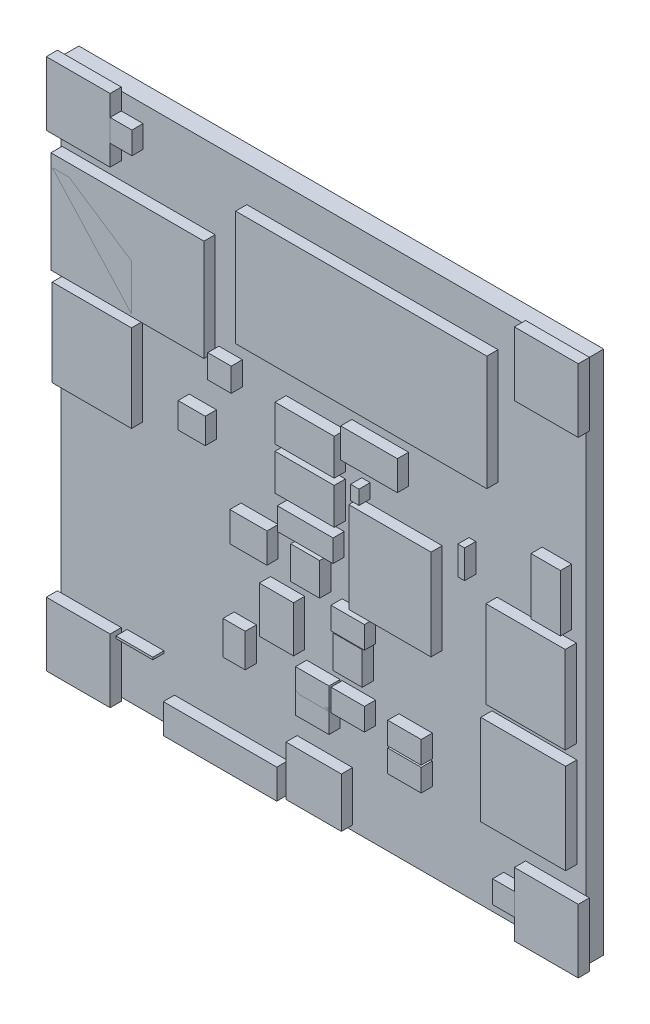
SolidWorks part; units mm, degrees
ref_plane "Front Plane" through (0, 0, 0) normal (0, 0, 1) x (1, 0, 0)
ref_plane "Top Plane" through (0, 0, 0) normal (0, 1, 0) x (1, 0, 0)
ref_plane "Right Plane" through (0, 0, 0) normal (1, 0, 0) x (0, 0, -1)
sketch "Sketch1" plane through (0, 0, 0) normal (0, 0, 1) x (1, 0, 0)
  line L0 (0, 46.99) -> (46.99, 46.99)
  line L1 (46.99, 46.99) -> (46.99, 0)
  line L2 (46.99, 0) -> (0, 0)
  line L3 (0, 0) -> (0, 46.99)
extrude "BOARD" add sketch "Sketch1" along normal blind 1.6 separate body
ref_plane "Plane1" through (0, 0, 1.6) normal (0, 0, 1) x (1, 0, 0)
sketch "Sketch2" plane through (0, 0, 1.6) normal (0, 0, 1) x (1, 0, 0)
  line L0 (16.1165, 20.4135) -> (19.4435, 20.4135)
  line L1 (19.4435, 20.4135) -> (19.4435, 17.75)
  line L2 (19.4435, 17.75) -> (16.1165, 17.75)
  line L3 (16.1165, 17.75) -> (16.1165, 20.4135)
extrude "1210-1" add sketch "Sketch2" along normal blind 1 separate body
sketch "Sketch3" plane through (0, 0, 1.6) normal (0, 0, 1) x (1, 0, 0)
  line L0 (25.3584, 20.8356) -> (20.3616, 20.8356)
  line L1 (20.3616, 20.8356) -> (20.3616, 22.827)
  line L2 (20.3616, 22.827) -> (25.3584, 22.827)
  line L3 (25.3584, 22.827) -> (25.3584, 20.8356)
extrude "1206-1" add sketch "Sketch3" along normal blind 1 separate body
sketch "Sketch4" plane through (0, 0, 1.6) normal (0, 0, 1) x (1, 0, 0)
  line L0 (20.1584, 30.76) -> (25.46, 30.76)
  line L1 (25.46, 30.76) -> (25.46, 27.5084)
  line L2 (25.46, 27.5084) -> (20.1584, 27.5084)
  line L3 (20.1584, 27.5084) -> (20.1584, 30.76)
extrude "EIA3528-1" add sketch "Sketch4" along normal blind 1 separate body
sketch "Sketch5" plane through (0, 0, 1.6) normal (0, 0, 1) x (1, 0, 0)
  line L0 (20.1584, 26.95) -> (25.46, 26.95)
  line L1 (25.46, 26.95) -> (25.46, 23.6984)
  line L2 (25.46, 23.6984) -> (20.1584, 23.6984)
  line L3 (20.1584, 23.6984) -> (20.1584, 26.95)
extrude "EIA3528-2" add sketch "Sketch5" along normal blind 1 separate body
sketch "Sketch6" plane through (0, 0, 1.6) normal (0, 0, 1) x (1, 0, 0)
  line L0 (25.1716, 17.5184) -> (28.1684, 17.5184)
  line L1 (28.1684, 17.5184) -> (28.1684, 15.527)
  line L2 (28.1684, 15.527) -> (25.1716, 15.527)
  line L3 (25.1716, 15.527) -> (25.1716, 17.5184)
extrude "0603-CAP-1" add sketch "Sketch6" along normal blind 1 separate body
sketch "Sketch7" plane through (0, 0, 1.6) normal (0, 0, 1) x (1, 0, 0)
  line L0 (15.5016, 8.6616) -> (15.5016, 11.6584)
  line L1 (15.5016, 11.6584) -> (17.493, 11.6584)
  line L2 (17.493, 11.6584) -> (17.493, 8.6616)
  line L3 (17.493, 8.6616) -> (15.5016, 8.6616)
extrude "0603-CAP-2" add sketch "Sketch7" along normal blind 1 separate body
sketch "Sketch8" plane through (0, 0, 1.6) normal (0, 0, 1) x (1, 0, 0)
  line L0 (24.1554, 20.4724) -> (24.1554, 17.5514)
  line L1 (24.1554, 17.5514) -> (21.5646, 17.5514)
  line L2 (21.5646, 17.5514) -> (21.5646, 20.4724)
  line L3 (21.5646, 20.4724) -> (24.1554, 20.4724)
extrude "SOT23-1" add sketch "Sketch8" along normal blind 1 separate body
sketch "Sketch9" plane through (0, 0, 1.6) normal (0, 0, 1) x (1, 0, 0)
  line L0 (25.3746, 12.5476) -> (25.3746, 15.4686)
  line L1 (25.3746, 15.4686) -> (27.9654, 15.4686)
  line L2 (27.9654, 15.4686) -> (27.9654, 12.5476)
  line L3 (27.9654, 12.5476) -> (25.3746, 12.5476)
extrude "SOT23-2" add sketch "Sketch9" along normal blind 1 separate body
sketch "Sketch10" plane through (0, 0, 1.6) normal (0, 0, 1) x (1, 0, 0)
  line L0 (7.35, 43.45) -> (5.35, 43.45)
  line L1 (5.35, 43.45) -> (5.35, 45.45)
  line L2 (5.35, 45.45) -> (7.35, 45.45)
  line L3 (7.35, 45.45) -> (7.35, 43.45)
extrude "FIDUCIAL-1X2-1" add sketch "Sketch10" along normal blind 1 separate body
sketch "Sketch11" plane through (0, 0, 1.6) normal (0, 0, 1) x (1, 0, 0)
  line L0 (41.64, 1.54) -> (39.64, 1.54)
  line L1 (39.64, 1.54) -> (39.64, 3.54)
  line L2 (39.64, 3.54) -> (41.64, 3.54)
  line L3 (41.64, 3.54) -> (41.64, 1.54)
extrude "FIDUCIAL-1X2-2" add sketch "Sketch11" along normal blind 1 separate body
sketch "POWER_JACK_SMD-1 [0]" plane through (0, 0, 1.6) normal (0, 0, 1) x (1, 0, 0)
  line L0 (-0.0216, 18.5716) -> (14.88, 18.5716)
  line L1 (14.88, 18.5716) -> (14.88, 9.3684)
  line L2 (14.88, 9.3684) -> (-0.0216, 9.3684)
  line L3 (-0.0216, 9.3684) -> (-0.0216, 18.5716)
sketch "Sketch14" plane through (0, 0, 1.6) normal (0, 0, 1) x (1, 0, 0)
  line L0 (13.8016, 40.06) -> (13.8016, 30.9584)
  line L1 (13.8016, 30.9584) -> (0.1, 30.9584)
  line L2 (0.1, 30.9584) -> (0.1, 40.06)
  line L3 (0.1, 40.06) -> (13.8016, 40.06)
extrude "POWER_JACK_PTH-1" add sketch "Sketch14" along normal blind 1 separate body
sketch "Sketch15" plane through (0, 0, 1.6) normal (0, 0, 1) x (1, 0, 0)
  line L0 (46.18, 15.5316) -> (46.18, 7.43)
  line L1 (46.18, 7.43) -> (38.5784, 7.43)
  line L2 (38.5784, 7.43) -> (38.5784, 15.5316)
  line L3 (38.5784, 15.5316) -> (46.18, 15.5316)
extrude "JST-2-SMD-1" add sketch "Sketch15" along normal blind 1 separate body
sketch "Sketch16" plane through (0, 0, 1.6) normal (0, 0, 1) x (1, 0, 0)
  line L0 (20.32, -0.1016) -> (10.16, -0.1016)
  line L1 (10.16, -0.1016) -> (10.16, 2.54)
  line L2 (10.16, 2.54) -> (20.32, 2.54)
  line L3 (20.32, 2.54) -> (20.32, -0.1016)
extrude "1X04-1" add sketch "Sketch16" along normal blind 1 separate body
sketch "Sketch17" plane through (0, 0, 1.6) normal (0, 0, 1) x (1, 0, 0)
  line L0 (43.0784, 25.4) -> (43.0784, 30.48)
  line L1 (43.0784, 30.48) -> (45.72, 30.48)
  line L2 (45.72, 30.48) -> (45.72, 25.4)
  line L3 (45.72, 25.4) -> (43.0784, 25.4)
extrude "1X02-1" add sketch "Sketch17" along normal blind 1 separate body
sketch "Sketch18" plane through (0, 0, 1.6) normal (0, 0, 1) x (1, 0, 0)
  line L0 (39.0434, 16.773) -> (39.0434, 24.573)
  line L1 (39.0434, 24.573) -> (46.145, 24.573)
  line L2 (46.145, 24.573) -> (46.145, 16.773)
  line L3 (46.145, 16.773) -> (39.0434, 16.773)
extrude "SCREWTERMINAL-3_5MM-2-1" add sketch "Sketch18" along normal blind 1 separate body
sketch "Sketch19" plane through (0, 0, 1.6) normal (0, 0, 1) x (1, 0, 0)
  line L0 (7.3116, 38.98) -> (7.3116, 31.18)
  line L1 (7.3116, 31.18) -> (0.21, 31.18)
  line L2 (0.21, 31.18) -> (0.21, 38.98)
  line L3 (0.21, 38.98) -> (7.3116, 38.98)
extrude "SCREWTERMINAL-3_5MM-2-2" add sketch "Sketch19" along normal blind 1 separate body
sketch "Sketch20" plane through (0, 0, 1.6) normal (0, 0, 1) x (1, 0, 0)
  line L0 (7.3116, 30.09) -> (7.3116, 22.29)
  line L1 (7.3116, 22.29) -> (0.21, 22.29)
  line L2 (0.21, 22.29) -> (0.21, 30.09)
  line L3 (0.21, 30.09) -> (7.3116, 30.09)
extrude "SCREWTERMINAL-3_5MM-2-3" add sketch "Sketch20" along normal blind 1 separate body
sketch "Sketch21" plane through (0, 0, 1.6) normal (0, 0, 1) x (1, 0, 0)
  line L0 (11.4808, 26.543) -> (13.9192, 26.543)
  line L1 (13.9192, 26.543) -> (13.9192, 24.257)
  line L2 (13.9192, 24.257) -> (11.4808, 24.257)
  line L3 (11.4808, 24.257) -> (11.4808, 26.543)
extrude "SJ_2S-1" add sketch "Sketch21" along normal blind 1 separate body
sketch "Sketch22" plane through (0, 0, 1.6) normal (0, 0, 1) x (1, 0, 0)
  line L0 (16.24, 31.5865) -> (16.24, 29.475)
  line L1 (16.24, 29.475) -> (14.1384, 29.475)
  line L2 (14.1384, 29.475) -> (14.1384, 31.5865)
  line L3 (14.1384, 31.5865) -> (16.24, 31.5865)
extrude "SJ_2S-NO-1" add sketch "Sketch22" along normal blind 1 separate body
sketch "Sketch23" plane through (0, 0, 1.6) normal (0, 0, 1) x (1, 0, 0)
  line L0 (36.5252, 27.94) -> (37.1348, 27.94)
  line L1 (37.1348, 27.94) -> (37.1348, 25.4)
  line L2 (37.1348, 25.4) -> (36.5252, 25.4)
  line L3 (36.5252, 25.4) -> (36.5252, 27.94)
extrude "PTH-JUMPER-NC_BOTTOM_NO_SILK-1" add sketch "Sketch23" along normal blind 1 separate body
sketch "Sketch24" plane through (0, 0, 1.6) normal (0, 0, 1) x (1, 0, 0)
  line L0 (26.035, 31.8516) -> (31.115, 31.8516)
  line L1 (31.115, 31.8516) -> (31.115, 29.21)
  line L2 (31.115, 29.21) -> (26.035, 29.21)
  line L3 (26.035, 29.21) -> (26.035, 31.8516)
extrude "1X02-2" add sketch "Sketch24" along normal blind 1 separate body
sketch "Sketch25" plane through (0, 0, 1.6) normal (0, 0, 1) x (1, 0, 0)
  line L0 (26.7665, 17.9865) -> (26.7665, 26.1135)
  line L1 (26.7665, 26.1135) -> (34.13, 26.1135)
  line L2 (34.13, 26.1135) -> (34.13, 17.9865)
  line L3 (34.13, 17.9865) -> (26.7665, 17.9865)
extrude "CR75-1" add sketch "Sketch25" along normal blind 1 separate body
sketch "Sketch26" plane through (0, 0, 1.6) normal (0, 0, 1) x (1, 0, 0)
  line L0 (16.637, 43.808) -> (39.127, 43.808)
  line L1 (39.127, 43.808) -> (39.127, 33.528)
  line L2 (39.127, 33.528) -> (16.637, 33.528)
  line L3 (16.637, 33.528) -> (16.637, 43.808)
extrude "SFE_LOGO_NAME_FLAME__2-1" add sketch "Sketch26" along normal blind 1 separate body
sketch "Sketch27" plane through (0, 0, 1.6) normal (0, 0, 1) x (1, 0, 0)
  line L0 (21.1406, 4.8944) -> (26.1034, 4.8944)
  line L1 (26.1034, 4.8944) -> (26.1034, 0.443)
  line L2 (26.1034, 0.443) -> (21.1406, 0.443)
  line L3 (21.1406, 0.443) -> (21.1406, 4.8944)
extrude "OSHW-LOGO-M-1" add sketch "Sketch27" along normal blind 1 separate body
sketch "Sketch28" plane through (0, 0, 0) normal (0, 0, 1) x (1, 0, 0)
  line L0 (4.0288, 9.1088) -> (1.0512, 9.1088)
  line L1 (1.0512, 9.1088) -> (1.0512, 6.438)
  line L2 (1.0512, 6.438) -> (4.0288, 6.438)
  line L3 (4.0288, 6.438) -> (4.0288, 9.1088)
extrude "OSHW-LOGO-S-1" add sketch "Sketch28" against normal blind 1 separate body
sketch "Sketch29" plane through (0, 0, 0) normal (0, 0, 1) x (1, 0, 0)
  line L0 (40.64, 30.66) -> (7.39, 30.66)
  line L1 (7.39, 30.66) -> (7.39, 15.24)
  line L2 (7.39, 15.24) -> (40.64, 15.24)
  line L3 (40.64, 15.24) -> (40.64, 30.66)
extrude "SFE_LOGO_NAME_FLAME__3-1" add sketch "Sketch29" against normal blind 1 separate body
sketch "Sketch30" plane through (0, 0, 1.6) normal (0, 0, 1) x (1, 0, 0)
  line L0 (27.6812, 26.5018) -> (26.9288, 26.5018)
  line L1 (26.9288, 26.5018) -> (26.9288, 27.778)
  line L2 (26.9288, 27.778) -> (27.6812, 27.778)
  line L3 (27.6812, 27.778) -> (27.6812, 26.5018)
extrude "0805-1" add sketch "Sketch30" along normal blind 1 separate body
sketch "Sketch31" plane through (0, 0, 1.6) normal (0, 0, 1) x (1, 0, 0)
  line L0 (25.1716, 11.1684) -> (28.1684, 11.1684)
  line L1 (28.1684, 11.1684) -> (28.1684, 9.177)
  line L2 (28.1684, 9.177) -> (25.1716, 9.177)
  line L3 (25.1716, 9.177) -> (25.1716, 11.1684)
extrude "0603-RES-1" add sketch "Sketch31" along normal blind 1 separate body
sketch "Sketch32" plane through (0, 0, 1.6) normal (0, 0, 1) x (1, 0, 0)
  line L0 (21.9966, 9.3904) -> (24.9934, 9.3904)
  line L1 (24.9934, 9.3904) -> (24.9934, 7.399)
  line L2 (24.9934, 7.399) -> (21.9966, 7.399)
  line L3 (21.9966, 7.399) -> (21.9966, 9.3904)
extrude "0603-RES-2" add sketch "Sketch32" along normal blind 1 separate body
sketch "Sketch33" plane through (0, 0, 1.6) normal (0, 0, 1) x (1, 0, 0)
  line L0 (21.9966, 11.1684) -> (24.9934, 11.1684)
  line L1 (24.9934, 11.1684) -> (24.9934, 9.177)
  line L2 (24.9934, 9.177) -> (21.9966, 9.177)
  line L3 (21.9966, 9.177) -> (21.9966, 11.1684)
extrude "0603-RES-3" add sketch "Sketch33" along normal blind 1 separate body
sketch "Sketch34" plane through (0, 0, 1.6) normal (0, 0, 1) x (1, 0, 0)
  line L0 (33.2484, 9.1516) -> (30.2516, 9.1516)
  line L1 (30.2516, 9.1516) -> (30.2516, 11.143)
  line L2 (30.2516, 11.143) -> (33.2484, 11.143)
  line L3 (33.2484, 11.143) -> (33.2484, 9.1516)
extrude "0603-RES-4" add sketch "Sketch34" along normal blind 1 separate body
sketch "Sketch35" plane through (0, 0, 1.6) normal (0, 0, 1) x (1, 0, 0)
  line L0 (33.2484, 6.9926) -> (30.2516, 6.9926)
  line L1 (30.2516, 6.9926) -> (30.2516, 8.984)
  line L2 (30.2516, 8.984) -> (33.2484, 8.984)
  line L3 (33.2484, 8.984) -> (33.2484, 6.9926)
extrude "0603-RES-5" add sketch "Sketch35" along normal blind 1 separate body
sketch "Sketch36" plane through (0, 0, 1.6) normal (0, 0, 1) x (1, 0, 0)
  line L0 (5.9184, 5.5116) -> (9.22, 5.5116)
  line L1 (9.22, 5.5116) -> (9.22, 5.3084)
  line L2 (9.22, 5.3084) -> (5.9184, 5.3084)
  line L3 (5.9184, 5.3084) -> (5.9184, 5.5116)
extrude "TRIMPOT-3MM-1" add sketch "Sketch36" along normal blind 1 separate body
sketch "Sketch37" plane through (0, 0, 1.6) normal (0, 0, 1) x (1, 0, 0)
  line L0 (-0.3175, 5.3975) -> (5.3975, 5.3975)
  line L1 (5.3975, 5.3975) -> (5.3975, -0.3175)
  line L2 (5.3975, -0.3175) -> (-0.3175, -0.3175)
  line L3 (-0.3175, -0.3175) -> (-0.3175, 5.3975)
extrude "STAND-OFF-1" add sketch "Sketch37" along normal blind 1 separate body
sketch "Sketch38" plane through (0, 0, 1.6) normal (0, 0, 1) x (1, 0, 0)
  line L0 (-0.3175, 47.3075) -> (5.3975, 47.3075)
  line L1 (5.3975, 47.3075) -> (5.3975, 41.5925)
  line L2 (5.3975, 41.5925) -> (-0.3175, 41.5925)
  line L3 (-0.3175, 41.5925) -> (-0.3175, 47.3075)
extrude "STAND-OFF-2" add sketch "Sketch38" along normal blind 1 separate body
sketch "Sketch39" plane through (0, 0, 1.6) normal (0, 0, 1) x (1, 0, 0)
  line L0 (41.5925, 47.3075) -> (47.3075, 47.3075)
  line L1 (47.3075, 47.3075) -> (47.3075, 41.5925)
  line L2 (47.3075, 41.5925) -> (41.5925, 41.5925)
  line L3 (41.5925, 41.5925) -> (41.5925, 47.3075)
extrude "STAND-OFF-3" add sketch "Sketch39" along normal blind 1 separate body
sketch "Sketch40" plane through (0, 0, 1.6) normal (0, 0, 1) x (1, 0, 0)
  line L0 (41.5925, 5.3975) -> (47.3075, 5.3975)
  line L1 (47.3075, 5.3975) -> (47.3075, -0.3175)
  line L2 (47.3075, -0.3175) -> (41.5925, -0.3175)
  line L3 (41.5925, -0.3175) -> (41.5925, 5.3975)
extrude "STAND-OFF-4" add sketch "Sketch40" along normal blind 1 separate body
sketch "Sketch41" plane through (0, 0, 1.6) normal (0, 0, 1) x (1, 0, 0)
  line L0 (18.7565, 16.0335) -> (21.82, 16.0335)
  line L1 (21.82, 16.0335) -> (21.82, 11.9065)
  line L2 (21.82, 11.9065) -> (18.7565, 11.9065)
  line L3 (18.7565, 11.9065) -> (18.7565, 16.0335)
extrude "MSOP-12_GND-1" add sketch "Sketch41" along normal blind 1 separate body
